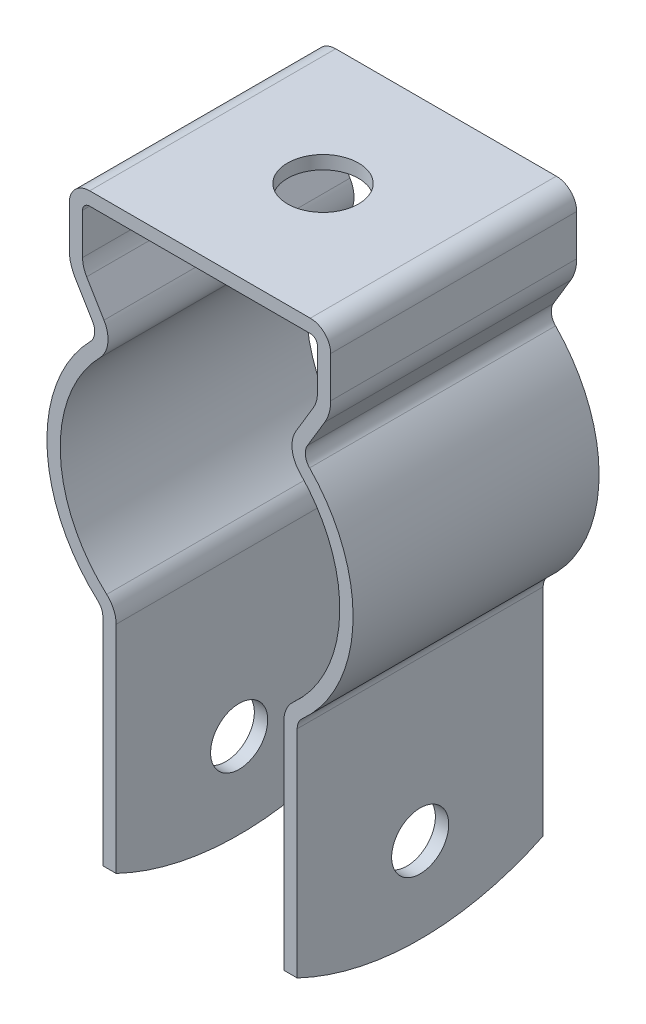
SolidWorks part; units mm, degrees
ref_plane "Front Plane" through (0, 0, 0) normal (0, 0, 1) x (1, 0, 0)
ref_plane "Top Plane" through (0, 0, 0) normal (0, 1, 0) x (1, 0, 0)
ref_plane "Right Plane" through (0, 0, 0) normal (1, 0, 0) x (0, 0, -1)
sketch "Sketch2" plane through (0, 0, 0) normal (0, 0, 1) x (1, 0, 0)
  line L0 (0, 0) -> (0, 54.7582) construction
  line L1 (-9.865, 20) -> (9.865, 20)
  line L2 (10.5, 19.365) -> (10.5, 15.7035)
  line L3 (10.138, 14.3967) -> (8.5864, 11.8106)
  line L4 (-10.5, 19.365) -> (-10.5, 15.7035)
  line L5 (-10.138, 14.3967) -> (-8.5864, 11.8106)
  line L6 (7.5, -11.1982) -> (7.5, -33)
  line L7 (-7.5, -11.1982) -> (-7.5, -33)
  line L8 (-8.6906, -11.1982) -> (-8.6906, -33)
  line L9 (-11.159, 13.7841) -> (-9.6073, 11.198)
  line L10 (-11.6906, 19.365) -> (-11.6906, 15.7035)
  line L11 (-9.865, 21.1906) -> (9.865, 21.1906)
  line L12 (11.6906, 19.365) -> (11.6906, 15.7035)
  line L13 (11.159, 13.7841) -> (9.6073, 11.198)
  line L14 (8.6906, -11.1982) -> (8.6906, -33)
  line L15 (-8.6906, -33) -> (-7.5, -33)
  line L16 (7.5, -33) -> (8.6906, -33)
  circle A0 centre (0, 0) radius 12.5 construction
  arc A1 (-8.9465, 8.7299) -> (-8.3444, -9.307) centre (0, 0) ccw
  arc A2 (8.9465, 8.7299) -> (8.3444, -9.307) centre (0, 0) cw
  arc A3 (-10.5, 15.7035) -> (-10.138, 14.3967) centre (-7.96, 15.7035) ccw
  arc A4 (10.5, 15.7035) -> (10.138, 14.3967) centre (7.96, 15.7035) cw
  arc A5 (8.3444, -9.307) -> (7.5, -11.1982) centre (10.04, -11.1982) ccw
  arc A6 (-8.3444, -9.307) -> (-7.5, -11.1982) centre (-10.04, -11.1982) cw
  arc A7 (8.5864, 11.8106) -> (8.9465, 8.7299) centre (10.7644, 10.5038) ccw
  arc A8 (-8.5864, 11.8106) -> (-8.9465, 8.7299) centre (-10.7644, 10.5038) cw
  arc A9 (9.865, 20) -> (10.5, 19.365) centre (9.865, 19.365) cw
  arc A10 (-9.865, 20) -> (-10.5, 19.365) centre (-9.865, 19.365) ccw
  arc A11 (-9.1392, -10.1935) -> (-8.6906, -11.1982) centre (-10.04, -11.1982) cw
  arc A12 (-9.7986, 9.5614) -> (-9.1392, -10.1935) centre (0, 0) ccw
  arc A13 (-9.6073, 11.198) -> (-9.7986, 9.5614) centre (-10.7644, 10.5038) cw
  arc A14 (-11.6906, 15.7035) -> (-11.159, 13.7841) centre (-7.96, 15.7035) ccw
  arc A15 (-9.865, 21.1906) -> (-11.6906, 19.365) centre (-9.865, 19.365) ccw
  arc A16 (9.865, 21.1906) -> (11.6906, 19.365) centre (9.865, 19.365) cw
  arc A17 (11.6906, 15.7035) -> (11.159, 13.7841) centre (7.96, 15.7035) cw
  arc A18 (9.6073, 11.198) -> (9.7986, 9.5614) centre (10.7644, 10.5038) ccw
  arc A19 (9.7986, 9.5614) -> (9.1392, -10.1935) centre (0, 0) cw
  arc A20 (9.1392, -10.1935) -> (8.6906, -11.1982) centre (10.04, -11.1982) ccw
  point P8 (0, 20)
  point P35 (-10.5, 15)
  point P38 (10.5, 15)
  point P41 (7.5, -10)
  point P44 (-7.5, -10)
  point P47 (7.5, 10)
  point P50 (-7.5, 10)
  point P53 (10.5, 20)
  point P56 (-10.5, 20)
  dimension "D1" = 25
  dimension "D8" = 2.54
  dimension "D9" = 0.635
  dimension "D2" = 23
  dimension "D3" = 15
  dimension "D4" = 21
  dimension "D5" = 5
  dimension "D6" = 5
  dimension "D7" = 15
  dimension "D10" = 1.1906
extrude "Boss-Extrude2" add sketch "Sketch2" along normal mid plane 22
sketch "Sketch4" plane through (0, 21.1906, 0) normal (0, 1, 0) x (1, 0, 0)
  point P0 (0, 0)
hole_wizard "1/4 (0.25) Diameter Hole1" positions "3DSketch1" profile "Sketch5" hole size "1/4" standard "ANSI Inch" end condition through all
sketch3d "3DSketch1"
  point P0 (0, 21.1906, 0)
sketch "Sketch5" plane through (0, 21.1906, 0) normal (1, 0, 0) x (0, 0, 1)
  line L0 (0, 0) -> (0, 54.1906)
  line L1 (0, 54.1906) -> (3.175, 54.1906)
  line L2 (3.175, 54.1906) -> (3.175, 0)
  line L5 (3.175, 0) -> (0, 0)
  line L11 (0, -6.35) -> (0, 107.95) construction
  dimension "Thru Hole Dia." = 6.35
  dimension "Thru Hole Depth" = 54.1906
sketch "Sketch6" plane through (8.6906, 0, 0) normal (1, 0, 0) x (0, 0, -1)
  line L0 (-11, -33) -> (11, -33) construction
  line L1 (11, -33) -> (11, -11.1982) construction
  line L2 (-11, -33) -> (-11, -11.1982) construction
  line L7 (11, -33) -> (11, -11.1982)
  line L8 (11, -11.1982) -> (-11, -11.1982)
  line L9 (-11, -11.1982) -> (-11, -33)
  line L10 (-11, -33) -> (11, -33)
  line L11 (11, -33) -> (11, -11.1982)
  line L12 (11, -11.1982) -> (-11, -11.1982)
  line L13 (-11, -11.1982) -> (-11, -33)
  line L14 (-11, -33) -> (11, -33)
  circle A0 centre (0, -7.55) radius 25.45
  point P0 (0, -25.38)
  point P3 (11, -30.5)
  point P4 (0, -33)
  point P7 (-11, -30.5)
  line M6 (11, -33) -> (11, -11.1982)
  line M9 (-11, -33) -> (11, -33)
  dimension "D1" = 7.62
  dimension "D2" = 2.5
  dimension "D3" = 0
extrude "Cut-Extrude1" cut sketch "Sketch6" against normal through all contours A0 L13 M9 | A0 L14 M6
hole_wizard "1/4-20 Tapped Hole1" positions "3DSketch2" profile "Sketch8" tap size "1/4-20" standard "ANSI Inch" end condition through all
sketch3d "3DSketch2"
  point P0 (8.6906, -25.38, 0)
sketch "Sketch8" plane through (8.6906, -25.38, 0) normal (0, 1, 0) x (0, 0, -1)
  line L0 (0, 0) -> (0, 22.3813)
  line L1 (0, 22.3813) -> (2.5527, 22.3813)
  line L2 (2.5527, 22.3813) -> (2.5527, 0)
  line L5 (2.5527, 0) -> (0, 0)
  line L11 (0, -6.35) -> (0, 107.95) construction
  dimension "Thru Tap Drill Dia." = 5.1054
  dimension "Thru Tap Drill Depth" = 22.3813
cosmetic thread "Hole Thread1" parameters "D2"=6.35
equation "\"D1@Sketch2\"=25mm"
equation "\"D2@Sketch2\"=23mm"
equation "\"D3@Sketch2\"=15mm"
equation "\"D4@Sketch2\"=21mm"
equation "\"D5@Sketch2\"=5mm"
equation "\"D6@Sketch2\"=5mm"
equation "\"D7@Sketch2\"=15mm"
equation "\"D10@Sketch2\"=3/64"
equation "\"D1@Boss-Extrude2\"=22mm"
equation "\"D1@Sketch6\"=.3in"
equation "\"D2@Sketch6\"=2.5mm"
